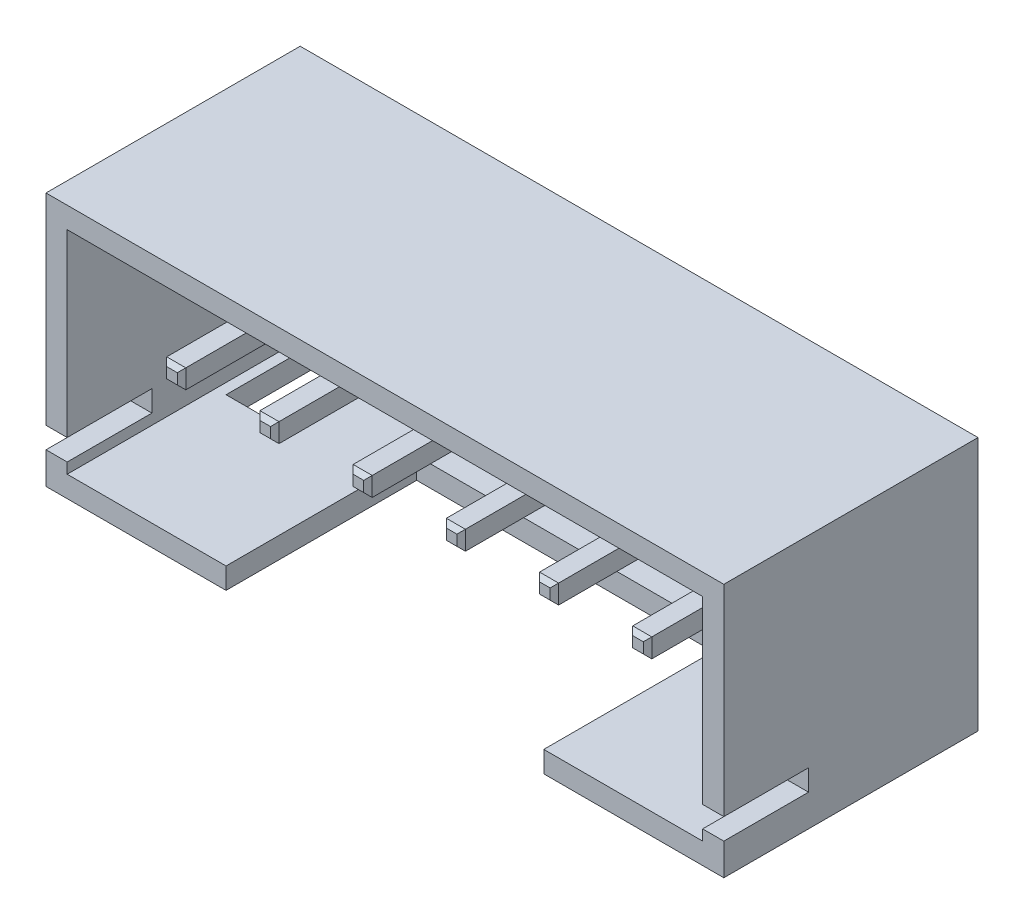
SolidWorks part; units mm, degrees
material "ABS"
ref_plane "Płaszczyzna przednia" through (0, 0, 0) normal (0, 0, 1) x (1, 0, 0)
ref_plane "Płaszczyzna górna" through (0, 0, 0) normal (0, 1, 0) x (1, 0, 0)
ref_plane "Płaszczyzna prawa" through (0, 0, 0) normal (1, 0, 0) x (0, 0, -1)
sketch "Szkic1" plane through (0, 0, 0) normal (0, 0, 1) x (1, 0, 0)
  line L1 (-8, -3) -> (8, -3)
  line L2 (-8, -3) -> (-8, 3)
  line L3 (-8, 3) -> (8, 3)
  line L4 (8, -3) -> (8, 3)
  line L5 (0, 3) -> (0, -3) construction
  line L6 (-8, 0) -> (8, 0) construction
  point P0 (0, 0)
  dimension "D1" = 16
  dimension "D2" = 6
extrude "Dodanie-wyciągnięcie1" add sketch "Szkic1" along normal blind 6
sketch "Szkic2" plane through (0, 0, 6) normal (0, 0, 1) x (1, 0, 0)
  line L0 (8, 3) -> (-8, 3) construction
  line L1 (-7.5, -2.5) -> (7.5, -2.5)
  line L2 (-7.5, -2.5) -> (-7.5, 2.5)
  line L3 (-7.5, 2.5) -> (7.5, 2.5)
  line L4 (7.5, -2.5) -> (7.5, 2.5)
  line L5 (0, 2.5) -> (0, -2.5) construction
  line L6 (-7.5, 0) -> (7.5, 0) construction
  line L7 (8, -3) -> (8, 3) construction
  point P0 (0, 0)
  dimension "D1" = 0.5
  dimension "D2" = 0.5
extrude "Wytnij-wyciągnięcie1" cut sketch "Szkic2" against normal offset from surface (5.5 mm away) 0.5 up to face at (0, 0, 0)
sketch "Szkic3" plane through (8, 0, 0) normal (1, 0, 0) x (0, 0, -1)
  line L0 (-6, -3) -> (-6, 3) construction
  line L1 (-6, -2.25) -> (-4, -2.25)
  line L2 (-6, -2.25) -> (-6, -1.75)
  line L3 (-6, -1.75) -> (-4, -1.75)
  line L4 (-4, -2.25) -> (-4, -1.75)
  line L5 (-6, -3) -> (0, -3) construction
  dimension "D1" = 0.75
  dimension "D2" = 2
  dimension "D3" = 0.5
extrude "Wytnij-wyciągnięcie2" cut sketch "Szkic3" against normal through all
sketch "Szkic4" plane through (0, -3, 0) normal (0, -1, 0) x (1, 0, 0)
  line L0 (-8, 6) -> (8, 6) construction
  line L1 (-3.75, 6) -> (3.75, 6)
  line L2 (-3.75, 6) -> (-3.75, 1.5)
  line L3 (-3.75, 1.5) -> (3.75, 1.5)
  line L4 (3.75, 6) -> (3.75, 1.5)
  point P6 (0, 1.5)
  dimension "D1" = 7.5
  dimension "D2" = 4.5
extrude "Wytnij-wyciągnięcie3" cut sketch "Szkic4" against normal up to next
sketch "Szkic5" plane through (0, -3, 0) normal (0, -1, 0) x (1, 0, 0)
  line L0 (0, 0) -> (0, 6) construction
  line L1 (7.5, 6) -> (-7.5, 6) construction
  line L3 (-7.25, 0.5) -> (-6.25, 0.5)
  line L4 (-7.25, 0.5) -> (-7.25, 2.5)
  line L5 (-7.25, 2.5) -> (-6.25, 2.5)
  line L6 (-6.25, 0.5) -> (-6.25, 2.5)
  line L7 (-8, 6) -> (-8, 0) construction
  line L8 (-8, 0) -> (8, 0) construction
  line L9 (6.25, 0.5) -> (6.25, 2.5)
  line L10 (7.25, 2.5) -> (6.25, 2.5)
  line L11 (7.25, 0.5) -> (7.25, 2.5)
  line L12 (7.25, 0.5) -> (6.25, 0.5)
  dimension "D1" = 0.75
  dimension "D2" = 1
  dimension "D3" = 0.5
  dimension "D4" = 2
extrude "Wytnij-wyciągnięcie4" cut sketch "Szkic5" against normal up to next
sketch "Szkic6" plane through (0, 0, 0.5) normal (0, 0, 1) x (1, 0, 0)
  line L0 (0, 0) -> (-7.5, 0) construction
  line L1 (-7.5, 2.5) -> (-7.5, -2.5) construction
  line L3 (-6, -0.225) -> (-5.55, -0.225)
  line L4 (-6, -0.225) -> (-6, 0.225)
  line L5 (-6, 0.225) -> (-5.55, 0.225)
  line L6 (-5.55, -0.225) -> (-5.55, 0.225)
  line L7 (-5.775, 0.225) -> (-5.775, -0.225) construction
  line L8 (-6, 0) -> (-5.55, 0) construction
  point P5 (-5.775, 0)
  dimension "D1" = 1.5
  dimension "D2" = 0.45
extrude "Dodanie-wyciągnięcie2" add sketch "Szkic6" along normal blind 4.75
chamfer "Sfazowanie1" distance 0.1 angle 45 4 edges at (-5.775, -0.225, 5.25) (-6, 0, 5.25) (-5.775, 0.225, 5.25) (-5.55, 0, 5.25)
pattern_linear "Szyk liniowy1" count 6 spacing 2.2 along (1, 0, 0) of "Dodanie-wyciągnięcie2", "Sfazowanie1"
